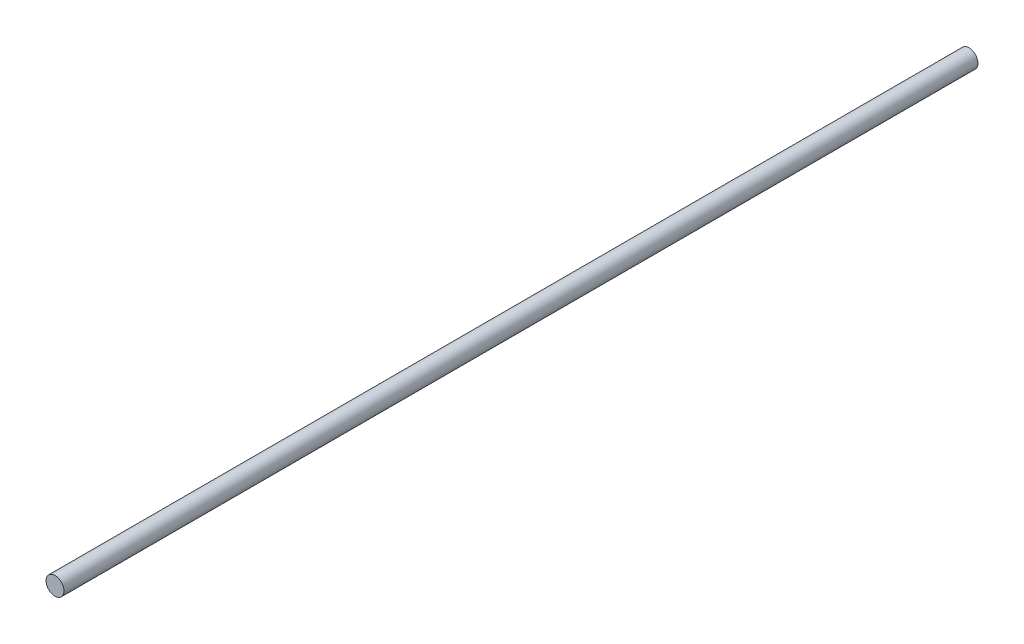
SolidWorks part; units mm, degrees
ref_plane "Plan de face" through (0, 0, 0) normal (0, 0, 1) x (1, 0, 0)
ref_plane "Plan de dessus" through (0, 0, 0) normal (0, 1, 0) x (1, 0, 0)
ref_plane "Plan de droite" through (0, 0, 0) normal (1, 0, 0) x (0, 0, -1)
sketch "Esquisse1" plane through (0, 0, 0) normal (0, 0, 1) x (1, 0, 0)
  circle A0 centre (-1.1513, 0.4941) radius 1.5
  dimension "D1" = 3
extrude "Boss.-Extru.1" add sketch "Esquisse1" along normal blind 152.5
